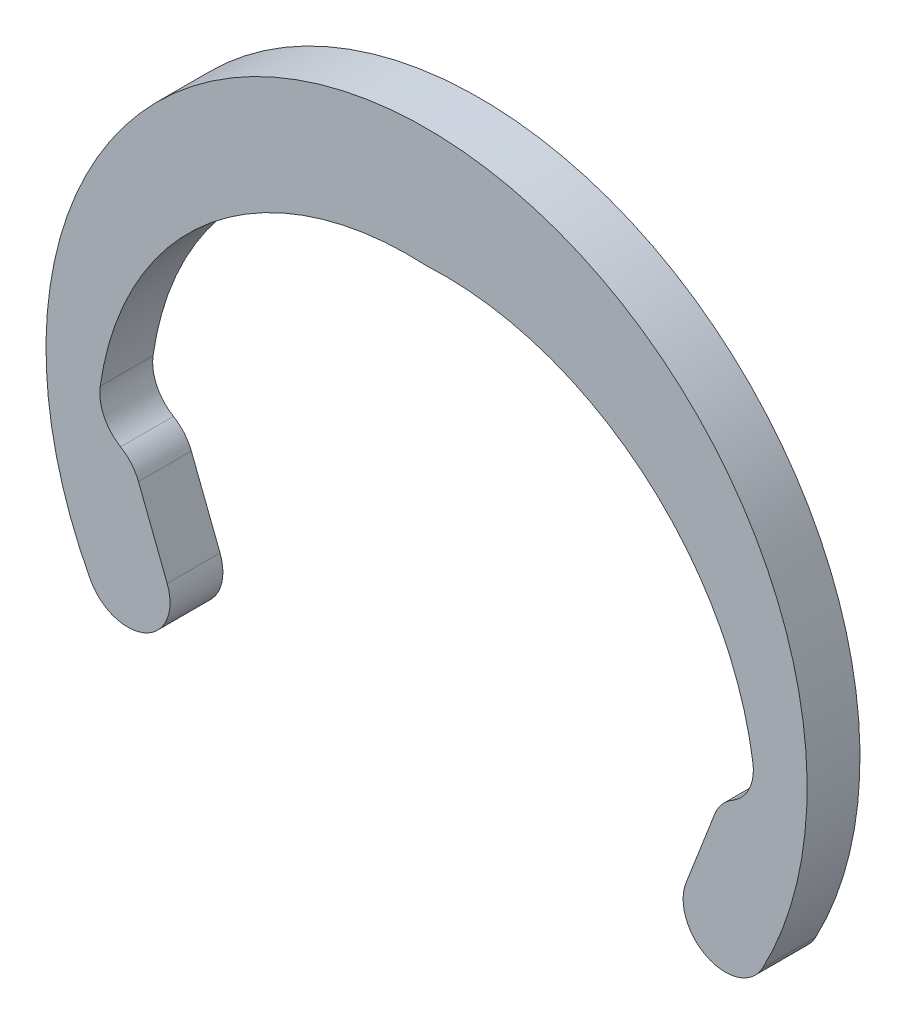
SolidWorks part; units mm, degrees
ref_plane "Plan de face" through (0, 0, 0) normal (0, 0, 1) x (1, 0, 0)
ref_plane "Plan de dessus" through (0, 0, 0) normal (0, 1, 0) x (1, 0, 0)
ref_plane "Plan de droite" through (0, 0, 0) normal (1, 0, 0) x (0, 0, -1)
sketch "Esquisse1" plane through (0, 0, 0) normal (0, 0, 1) x (1, 0, 0)
  line L0 (0, 0) -> (0, 62.0267) construction
  line L1 (-11.221, 7.2) -> (10.9542, 7.2) construction
  line L2 (-13.8095, -3.8) -> (15.5704, -3.8) construction
  line L3 (5.4506, -1.3121) -> (4.9076, -2.7104)
  line L4 (-5.4506, -1.3121) -> (-4.9076, -2.7104)
  arc A0 (6.36, -3.375) -> (-6.36, -3.375) centre (0, 0) ccw
  arc A1 (6.1744, -0.1115) -> (0, 4.9477) centre (0.3332, -0.9428) ccw
  arc A2 (4.9076, -2.7104) -> (6.36, -3.375) centre (5.6533, -3) ccw
  arc A3 (5.7893, -0.913) -> (5.4506, -1.3121) centre (6.1963, -1.6017) ccw
  arc A5 (6.1744, -0.1115) -> (5.7893, -0.913) centre (5.3824, -0.2243) cw
  arc A6 (-6.1744, -0.1115) -> (-5.7893, -0.913) centre (-5.3824, -0.2243) ccw
  arc A8 (-5.7893, -0.913) -> (-5.4506, -1.3121) centre (-6.1963, -1.6017) cw
  arc A9 (-4.9076, -2.7104) -> (-6.36, -3.375) centre (-5.6533, -3) cw
  arc A10 (-6.1744, -0.1115) -> (0, 4.9477) centre (-0.3332, -0.9428) cw
  dimension "D2" = 14.4
  dimension "D3" = 11.8
  dimension "D5" = 1.6
  dimension "D6" = 1.6
  dimension "D8" = 0.8
  dimension "D1" = 1
  dimension "D4" = 11
  dimension "D7" = 1.5
extrude "Extrusion1" add sketch "Esquisse1" along normal blind 1
